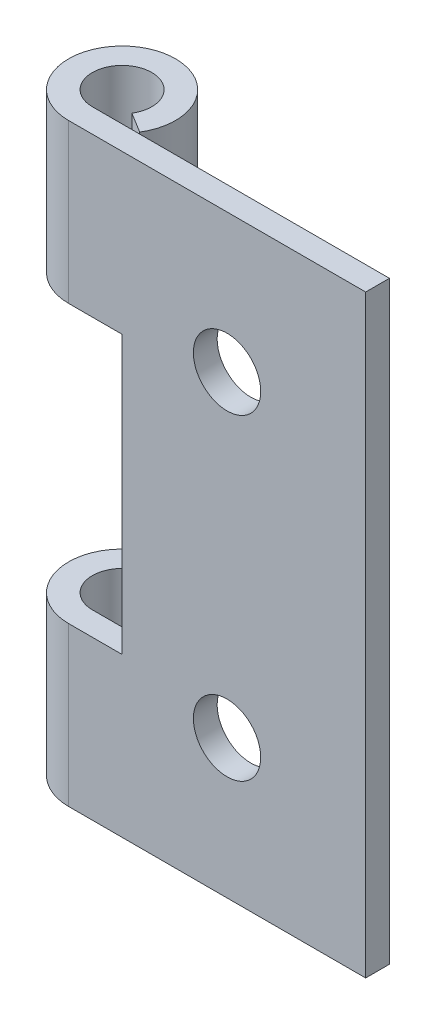
SolidWorks part; units mm, degrees
material "AISI 304"
ref_plane "Ön Düzlem" through (0, 0, 0) normal (0, 0, 1) x (1, 0, 0)
ref_plane "Üst Düzlem" through (0, 0, 0) normal (0, 1, 0) x (1, 0, 0)
ref_plane "Sağ Düzlem" through (0, 0, 0) normal (1, 0, 0) x (0, 0, -1)
sketch "Çizim1" plane through (0, 0, 0) normal (0, 1, 0) x (1, 0, 0)
  line L0 (0, 7.8372) -> (0, -8.9997) construction
  line L1 (0, 0.6) -> (15, 0.6)
  line L3 (0, -0.6) -> (15, -0.6)
  line L4 (15, 0.6) -> (15, -0.6)
  line L5 (0, 0) -> (15, -0.6) construction
  line L6 (0, 0) -> (15, 0.6) construction
  line L7 (2.3018, 0.6888) -> (1.2788, 1.316)
  arc A0 (2.3018, 0.6888) -> (0, -0.6) centre (0, 2.1) ccw
  arc A4 (1.2788, 1.316) -> (0, 0.6) centre (0, 2.1) ccw
  point P0 (0, 0)
  dimension "D1" = 2.7
  dimension "D2" = 1.2
extrude "Yükseklik-Ekstrüzyon1" add sketch "Çizim1" against normal blind 30
sketch "Çizim3" plane through (0, -30, 0) normal (0, -1, 0) x (1, 0, 0)
  line L0 (1.2788, -1.316) -> (2.3018, -0.6888) construction
  line L1 (1.2788, -1.316) -> (2.3018, -0.6888)
  line L3 (0, -0.6) -> (2.7, -0.6)
  line L4 (2.7, -0.6) -> (2.7, 0.6)
  line L5 (0, 0.6) -> (15, 0.6) construction
  line L6 (15, -0.6) -> (0, -0.6) construction
  line L7 (0, 0.6) -> (2.7, 0.6)
  arc A0 (0, -0.6) -> (1.2788, -1.316) centre (0, -2.1) ccw construction
  arc A1 (0, 0.6) -> (2.3018, -0.6888) centre (0, -2.1) ccw construction
  arc A2 (0, -0.6) -> (1.2788, -1.316) centre (0, -2.1) ccw
  arc A3 (0, 0.6) -> (2.3018, -0.6888) centre (0, -2.1) ccw
extrude "Kes-Ekstrüzyon2" cut sketch "Çizim3" against normal blind 14 from offset 8 offset against normal yes
sketch "Çizim4" plane through (0, 0, -0.6) normal (0, 0, -1) x (-1, 0, 0)
  line L0 (0, -30) -> (0, 0) construction
  line L1 (-2.7, -30) -> (2.7, -30) construction
  line L2 (-15, 0) -> (0, 0) construction
  circle A0 centre (-8, -23) radius 1.7
  circle A1 centre (-8, -7) radius 1.7
  dimension "D4" = 3.4
  dimension "D5" = 3.4
  dimension "D1" = 8
  dimension "D2" = 16
  dimension "D3" = 7
extrude "Kes-Ekstrüzyon3" cut sketch "Çizim4" against normal blind 1.2
